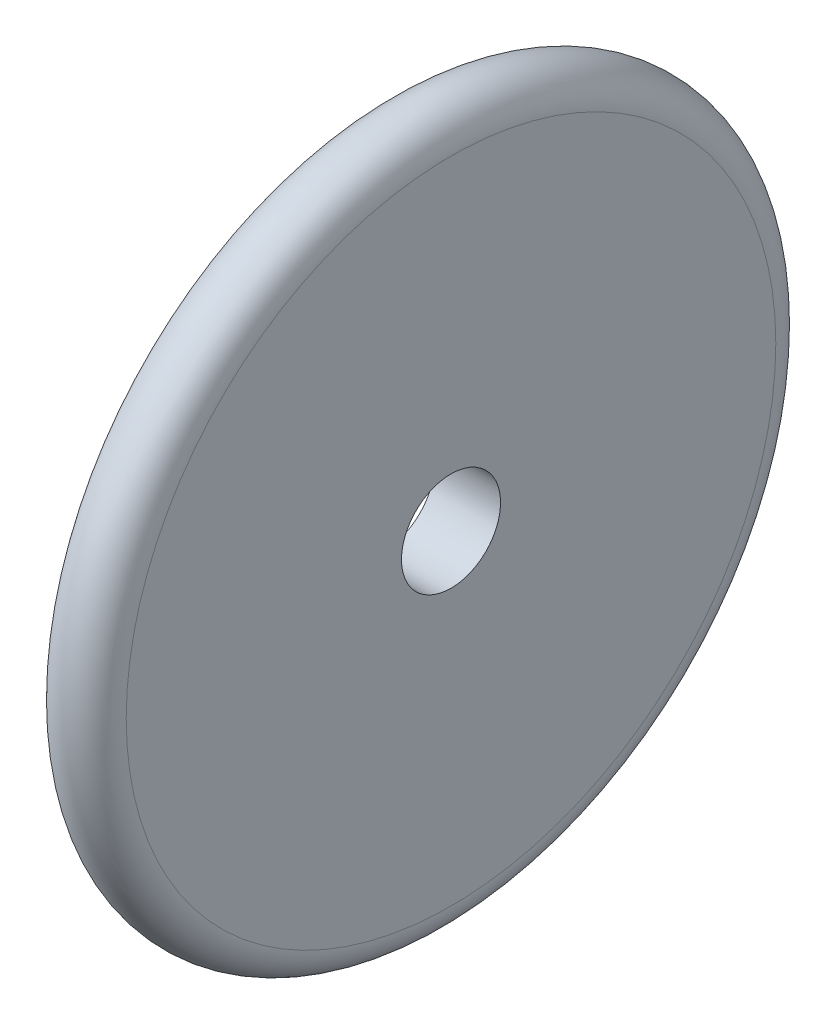
SolidWorks part; units mm, degrees
ref_plane "Front Plane" through (0, 0, 0) normal (0, 0, 1) x (1, 0, 0)
ref_plane "Top Plane" through (0, 0, 0) normal (0, 1, 0) x (1, 0, 0)
ref_plane "Right Plane" through (0, 0, 0) normal (1, 0, 0) x (0, 0, -1)
sketch "Sketch2" plane through (0, 0, 0) normal (0, 1, 0) x (1, 0, 0)
  line L0 (-9.525, 34.925) -> (9.525, 34.925) construction
  line L1 (9.525, -44.45) -> (-9.525, -44.45)
  line L2 (9.525, -44.45) -> (9.525, 34.925)
  line L3 (-9.525, -58.7375) -> (9.525, -58.7375) construction
  line L4 (-9.525, -44.45) -> (-9.525, 34.925)
  line L5 (9.525, -44.45) -> (-9.525, 44.45) construction
  line L6 (9.525, 44.45) -> (-9.525, -44.45) construction
  arc A0 (-9.525, 34.925) -> (9.525, 34.925) centre (0, 34.925) cw
  point P0 (0, 0)
  dimension "D1" = 19.05
  dimension "D2" = 88.9
  dimension "D3" = 9.525
  dimension "D4" = 14.2875
revolve "Revolve1" add sketch "Sketch2" angle 360 about L3
